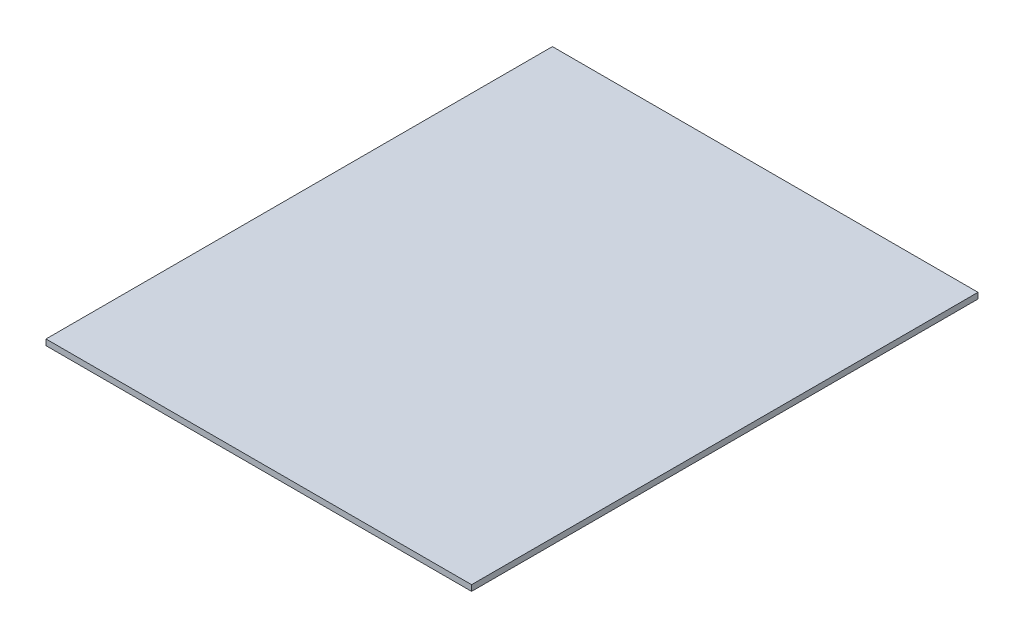
SolidWorks part; units mm, degrees
ref_plane "Front Plane" through (0, 0, 0) normal (0, 0, 1) x (1, 0, 0)
ref_plane "Top Plane" through (0, 0, 0) normal (0, 1, 0) x (1, 0, 0)
ref_plane "Right Plane" through (0, 0, 0) normal (1, 0, 0) x (0, 0, -1)
sketch "Sketch1" plane through (0, 0, 0) normal (0, 1, 0) x (1, 0, 0)
  line L1 (-109.25, 130) -> (109.25, 130)
  line L2 (-109.25, 130) -> (-109.25, -130)
  line L3 (-109.25, -130) -> (109.25, -130)
  line L4 (109.25, 130) -> (109.25, -130)
  line L5 (-109.25, 130) -> (109.25, -130) construction
  line L6 (-109.25, -130) -> (109.25, 130) construction
  point P0 (0, 0)
extrude "Boss-Extrude1" add sketch "Sketch1" along normal blind 3
